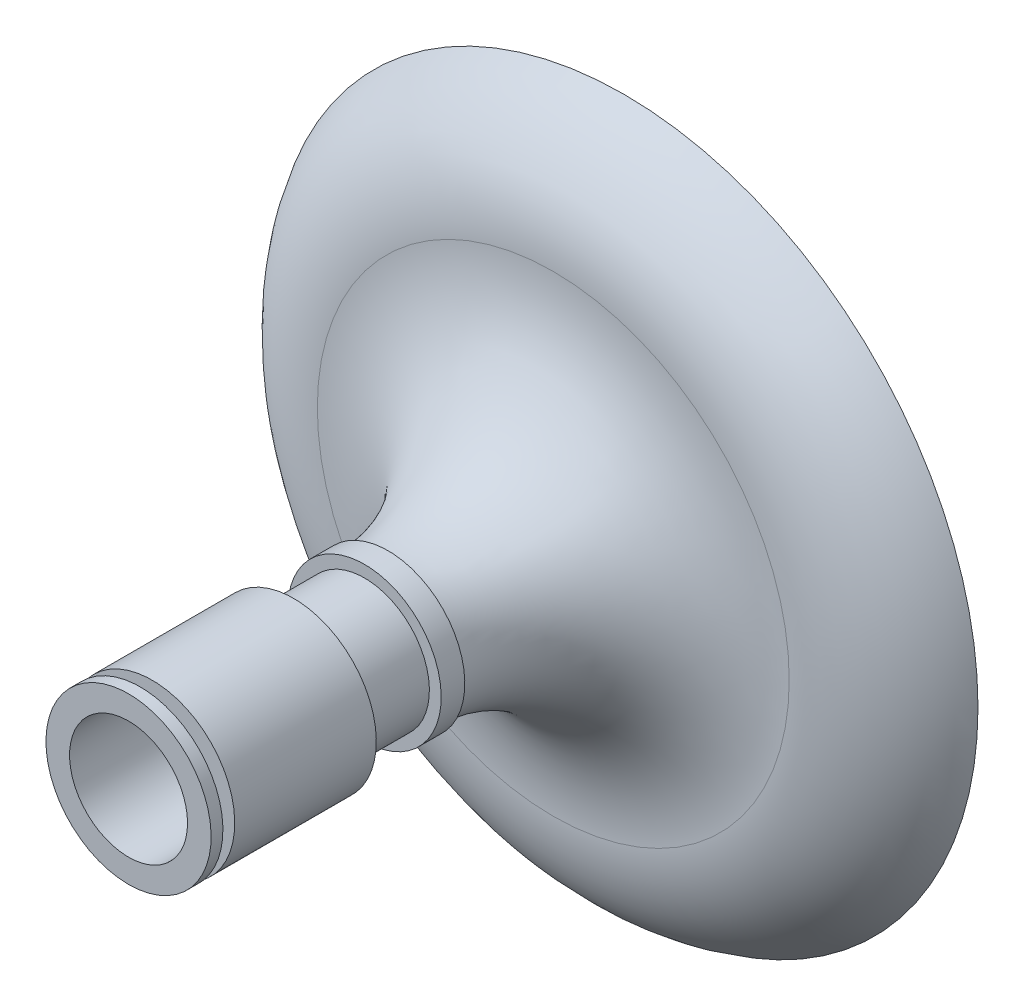
SolidWorks part; units mm, degrees
ref_plane "Front Plane" through (0, 0, 0) normal (1, 0, 0) x (0, 1, 0)
ref_plane "Top Plane" through (0, 0, 0) normal (0, 0, 1) x (0, 1, 0)
ref_plane "Right Plane" through (0, 0, 0) normal (0, 1, 0) x (-1, 0, 0)
sketch "Sketch1" plane through (0, 0, 0) normal (1, 0, 0) x (0, 1, 0)
  line L0 (0, 0) -> (0, -10) construction
  line L1 (0, -10) -> (-15, -10)
  line L2 (0, -7) -> (-10, -7) construction
  line L3 (0, 0) -> (-3, 0)
  line L4 (0, 0) -> (0, -10)
  arc A0 (-10, -7) -> (-15, -10) centre (-10, -12.6667) ccw
  arc A1 (-10, -7) -> (-3, 0) centre (-10, 0) ccw
  dimension "D1" = 15
  dimension "D2" = 10
  dimension "D3" = 3
  dimension "D4" = 3
revolve "Revolve1" add sketch "Sketch1" angle 360 about L4
shell "Shell1" thickness 1
sketch "Sketch2" plane through (0, 0, 0) normal (1, 0, 0) x (0, 1, 0)
  line L0 (0, 0) -> (-3.25, 0)
  line L1 (3, 0) -> (-3, 0) construction
  line L2 (-3.25, 0) -> (-3.25, 1)
  line L3 (-3.25, 1) -> (-2.75, 1)
  line L4 (-2.75, 1) -> (-2.75, 4)
  line L5 (-2.75, 4) -> (-3.5, 4)
  line L6 (-3.5, 4) -> (-3.5, 10)
  line L7 (-3.5, 10) -> (-2.75, 10)
  line L8 (0, 11) -> (0, 0)
  line L9 (-2.75, 10) -> (-2.75, 10.5)
  line L10 (-2.75, 10.5) -> (-3.5, 10.5)
  line L11 (-3.5, 10.5) -> (-3.5, 11)
  line L12 (-3.5, 11) -> (0, 11)
  dimension "D1" = 1
  dimension "D2" = 3
  dimension "D3" = 0.5
  dimension "D4" = 0.25
  dimension "D5" = 0.25
  dimension "D6" = 10
  dimension "D7" = 1
  dimension "D8" = 0.5
revolve "Revolve2" add sketch "Sketch2" angle 360 about L8
sketch "Sketch3" plane through (0, 0, 0) normal (0, 0, 1) x (0, 1, 0)
  circle A0 centre (0, 0) radius 2.5
  dimension "D1" = 5
extrude "Cut-Extrude1" cut sketch "Sketch3" against normal through all both and the other way through all
sketch "CUP" plane through (0, 0, -10) normal (0, 0, -1) x (1, 0, 0)
  point P0 (0, 0)
